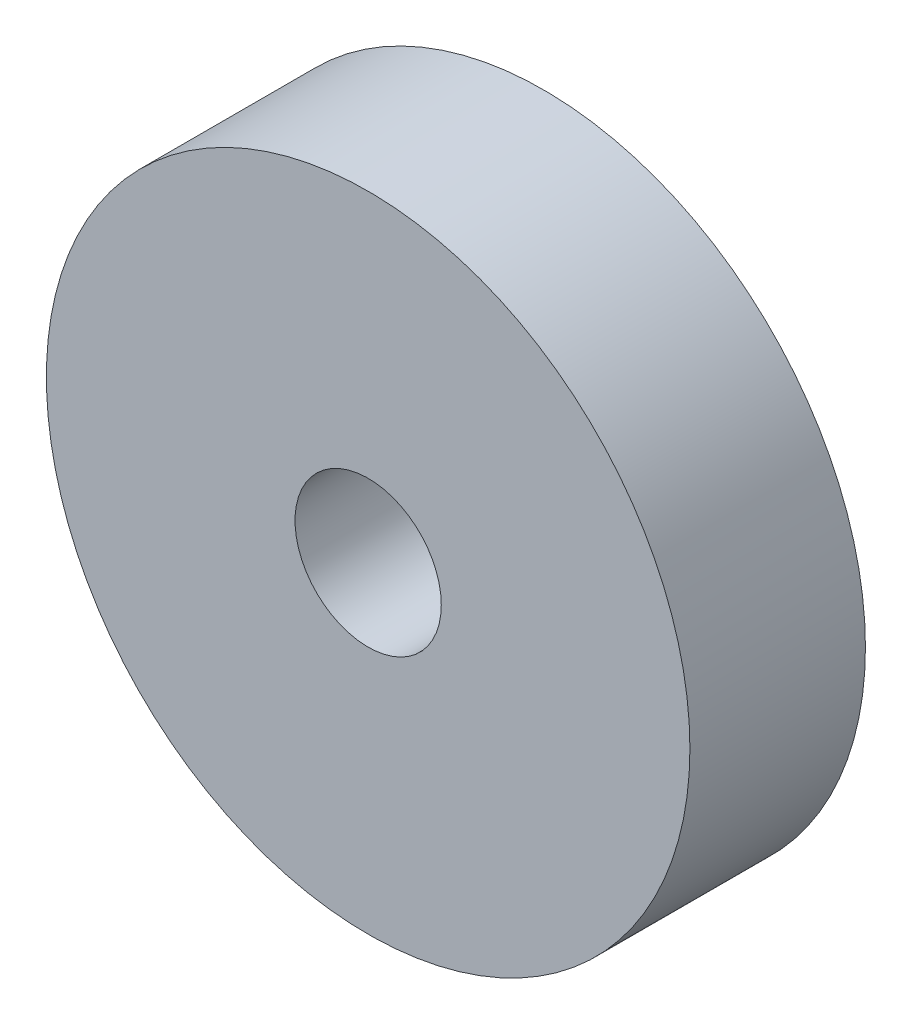
SolidWorks part; units mm, degrees
ref_plane "前基準面" through (0, 0, 0) normal (0, 0, 1) x (1, 0, 0)
ref_plane "上基準面" through (0, 0, 0) normal (0, 1, 0) x (1, 0, 0)
ref_plane "右基準面" through (0, 0, 0) normal (1, 0, 0) x (0, 0, -1)
sketch "草圖1" plane through (0, 0, 0) normal (0, 0, 1) x (1, 0, 0)
  circle A0 centre (0, 0) radius 5.5
  circle A1 centre (0, 0) radius 1.25
  dimension "D1" = 11
  dimension "D2" = 2.5
extrude "填料-伸長1" add sketch "草圖1" along normal blind 3
